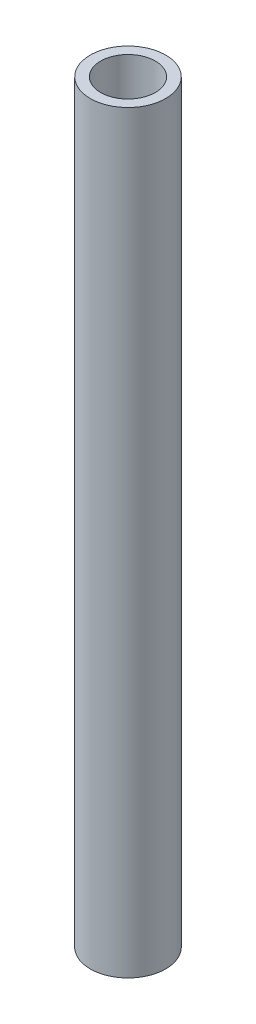
SolidWorks part; units mm, degrees
material "Pure Gold"
ref_plane "Front Plane" through (0, 0, 0) normal (0, 0, 1) x (1, 0, 0)
ref_plane "Top Plane" through (0, 0, 0) normal (0, 1, 0) x (1, 0, 0)
ref_plane "Right Plane" through (0, 0, 0) normal (1, 0, 0) x (0, 0, -1)
sketch "Sketch1" plane through (0, 0, 0) normal (0, 1, 0) x (1, 0, 0)
  circle A0 centre (0, 0) radius 4
  dimension "D1" = 8
extrude "Boss-Extrude1" add sketch "Sketch1" along normal blind 80
sketch "Sketch2" plane through (0, 80, 0) normal (0, 1, 0) x (1, 0, 0)
  circle A0 centre (0, 0) radius 2.8994
extrude "Cut-Extrude1" cut sketch "Sketch2" against normal blind 10
